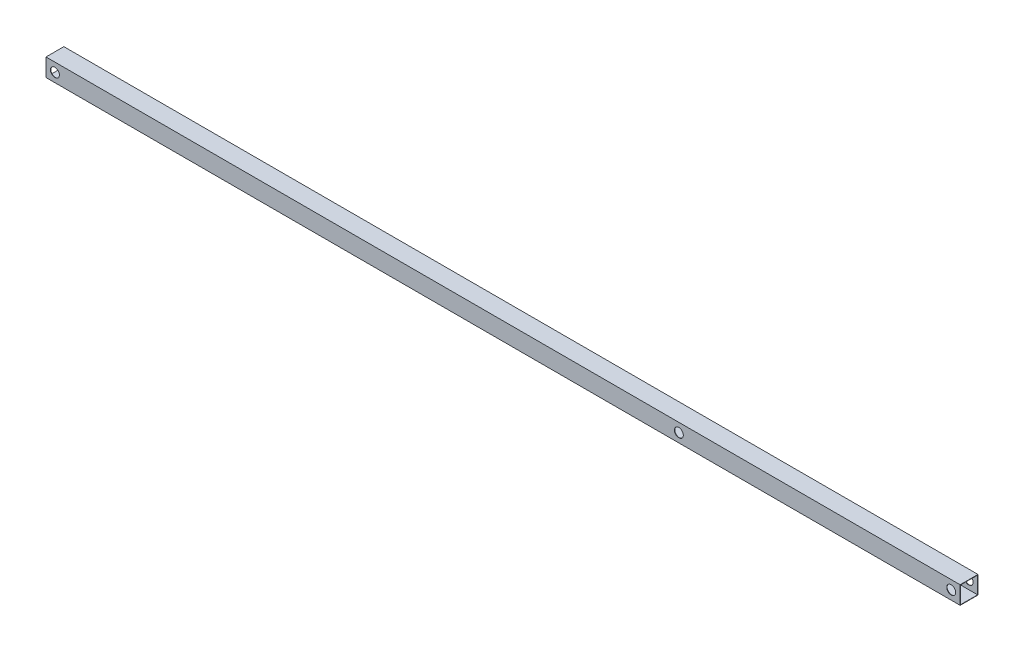
SolidWorks part; units mm, degrees
ref_plane "Alzado" through (0, 0, 0) normal (0, 0, 1) x (1, 0, 0)
ref_plane "Planta" through (0, 0, 0) normal (0, 1, 0) x (1, 0, 0)
ref_plane "Vista lateral" through (0, 0, 0) normal (1, 0, 0) x (0, 0, -1)
sketch "Croquis1" plane through (0, 0, 0) normal (0, 0, 1) x (1, 0, 0)
  line L0 (0, 0) -> (1300, 0)
  dimension "D1" = 1300
other "Al tube (square) 1 SQ X .022 WALL(3)"
ref_plane "Plano1" through (0, 0, 0) normal (1, 0, 0) x (0, 1, 0)
sketch "Sketch1" plane through (0, 0, 0) normal (1, 0, 0) x (0, 1, 0)
  line L0 (-12.1412, -12.1412) -> (-12.1412, 12.1412)
  line L1 (12.1412, 12.1412) -> (-12.1412, 12.1412)
  line L2 (12.1412, 12.1412) -> (12.1412, -12.1412)
  line L3 (-12.1412, -12.1412) -> (12.1412, -12.1412)
  line L4 (-12.7, -12.7) -> (12.7, -12.7)
  line L5 (-12.7, -12.7) -> (-12.7, 12.7)
  line L6 (12.7, 12.7) -> (-12.7, 12.7)
  line L7 (12.7, 12.7) -> (12.7, -12.7)
  line L8 (0, -12.1412) -> (0, -12.7) construction
  line L9 (0, -12.1412) -> (0, 12.1412) construction
  line L10 (0, 12.1412) -> (0, 12.7) construction
  line L11 (12.7, 0) -> (12.1412, 0) construction
  line L12 (12.1412, 0) -> (-12.1412, 0) construction
  line L13 (-12.1412, 0) -> (-12.7, 0) construction
  point P14 (0, 0)
  dimension "Thickness" = 0.5588
  dimension "V_leg" = 25.4
  dimension "H_leg" = 25.4
sketch "Croquis3" plane through (0, 0, 12.7) normal (0, 0, 1) x (1, 0, 0)
  line L0 (0, 0) -> (1300, 0) construction
  line L1 (1300, 12.7) -> (1300, -12.7) construction
  line L2 (0, 12.7) -> (0, -12.7) construction
  circle A0 centre (1287.3, 0) radius 6.35
  circle A1 centre (900, 0) radius 6.35
  circle A2 centre (12.7, 0) radius 6.35
  dimension "D1" = 12.7
  dimension "D2" = 12.7
  dimension "D3" = 400
  dimension "D4" = 12.7
extrude "Cortar-Extruir1" cut sketch "Croquis3" against normal through all
